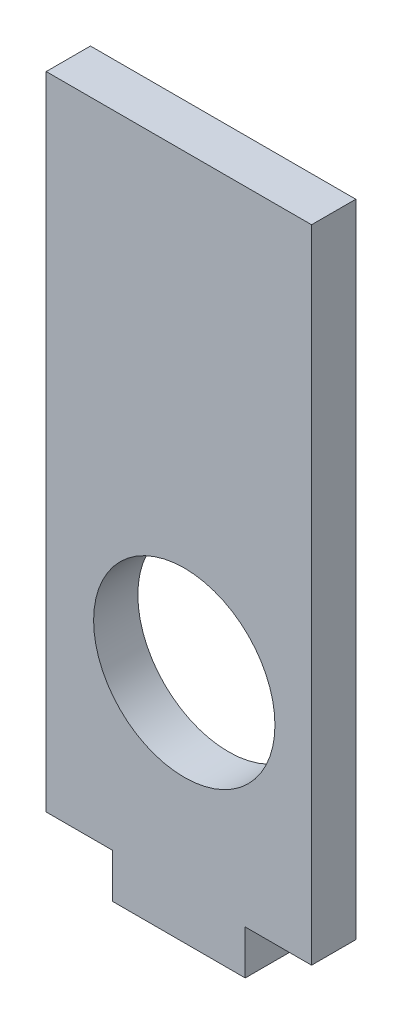
SolidWorks part; units mm, degrees
ref_plane "前视基准面" through (0, 0, 0) normal (0, 0, 1) x (1, 0, 0)
ref_plane "上视基准面" through (0, 0, 0) normal (0, 1, 0) x (1, 0, 0)
ref_plane "右视基准面" through (0, 0, 0) normal (1, 0, 0) x (0, 0, -1)
sketch "草图1" plane through (0, 0, 0) normal (0, 0, 1) x (1, 0, 0)
  line L0 (-6, 0) -> (-6, 15)
  line L1 (-6, 0) -> (-3, 0)
  line L3 (6, 0) -> (6, 15)
  line L4 (-3, 0) -> (-3, -2)
  line L6 (-3, -2) -> (3, -2)
  line L7 (3, 0) -> (3, -2)
  line L8 (-6, 15) -> (-6, 30.0788)
  line L9 (-6, 30.0788) -> (6, 30.0788)
  line L10 (6, 30.0788) -> (6, 15)
  line L11 (3, 0) -> (6, 0)
extrude "凸台-拉伸1" add sketch "草图1" along normal blind 2 contours L9 L10 L3 L11 L7 L6 L4 L1 L0 L8
sketch3d "3D草图1"
  spline S0 degree 3 poles (-3.7284, 8.6867, 2) (-3.7078, 8.161, 2) (-3.6722, 7.9035, 2) (-3.5524, 7.3986, 2) (-3.467, 7.1488, 2) (-3.2505, 6.6735, 2) (-3.1206, 6.4491, 2) (-2.8176, 6.0262, 2) (-2.6428, 5.8268, 2) (-2.2635, 5.4714, 2) (-2.0578, 5.3133, 2) (-1.6138, 5.037, 2) (-1.3773, 4.9208, 2) (-0.8916, 4.7388, 2) (-0.639, 4.6715, 2) (-0.1207, 4.5878, 2) (0.1386, 4.5724, 2) (0.6574, 4.5924, 2) (0.9199, 4.6288, 2) (1.4263, 4.7517, 2) (1.6711, 4.8374, 2) (2.144, 5.0577, 2) (2.3715, 5.1927, 2) (2.7898, 5.5003, 2) (2.9832, 5.6739, 2) (3.3378, 6.0622, 2) (3.4935, 6.271, 2) (3.7622, 6.715, 2) (3.8764, 6.9531, 2) (4.055, 7.4439, 2) (4.1196, 7.6952, 2) (4.2002, 8.2093, 2) (4.2156, 8.4739, 2) (4.1954, 8.9933, 2) (4.1605, 9.2504, 2) (4.0401, 9.7595, 2) (3.9548, 10.0085, 2) (3.7402, 10.4807, 2) (3.6098, 10.7071, 2) (3.304, 11.134, 2) (3.1327, 11.3292, 2) (2.7544, 11.6845, 2) (2.5446, 11.8459, 2) (2.1019, 12.1214, 2) (1.8693, 12.2361, 2) (1.3817, 12.4193, 2) (1.1256, 12.4874, 2) (0.6129, 12.5704, 2) (0.3537, 12.5866, 2) (-0.1705, 12.5666, 2) (-0.4299, 12.5305, 2) (-0.9342, 12.4086, 2) (-1.1829, 12.3219, 2) (-1.6571, 12.101, 2) (-1.8803, 11.9687, 2) (-2.2997, 11.661, 2) (-2.497, 11.4837, 2) (-2.8478, 11.0998, 2) (-3.0034, 10.8921, 2) (-3.2746, 10.4448, 2) (-3.3883, 10.2072, 2) (-3.5662, 9.7198, 2) (-3.6318, 9.4669, 2) (-3.7132, 8.9479, 2) (-3.7284, 8.6867, 2) (-3.7078, 8.161, 2) (-3.6722, 7.9035, 2) knots -0.03125 -0.03125 0 0 0.03125 0.03125 0.0625 0.0625 0.09375 0.09375 0.125 0.125 0.15625 0.15625 0.1875 0.1875 0.21875 0.21875 0.25 0.25 0.28125 0.28125 0.3125 0.3125 0.34375 0.34375 0.375 0.375 0.40625 0.40625 0.4375 0.4375 0.46875 0.46875 0.5 0.5 0.53125 0.53125 0.5625 0.5625 0.59375 0.59375 0.625 0.625 0.65625 0.65625 0.6875 0.6875 0.71875 0.71875 0.75 0.75 0.78125 0.78125 0.8125 0.8125 0.84375 0.84375 0.875 0.875 0.90625 0.90625 0.9375 0.9375 0.96875 0.96875 1 1 1.03125 1.03125 1.0625 only from (-3.7181, 8.4239, 2) to (-3.7181, 8.4239, 2)
  spline S1 degree 3 poles (-3.7284, 8.6867, 2) (-3.7078, 8.161, 2) (-3.6722, 7.9035, 2) (-3.5524, 7.3986, 2) (-3.467, 7.1488, 2) (-3.2505, 6.6735, 2) (-3.1206, 6.4491, 2) (-2.8176, 6.0262, 2) (-2.6428, 5.8268, 2) (-2.2635, 5.4714, 2) (-2.0578, 5.3133, 2) (-1.6138, 5.037, 2) (-1.3773, 4.9208, 2) (-0.8916, 4.7388, 2) (-0.639, 4.6715, 2) (-0.1207, 4.5878, 2) (0.1386, 4.5724, 2) (0.6574, 4.5924, 2) (0.9199, 4.6288, 2) (1.4263, 4.7517, 2) (1.6711, 4.8374, 2) (2.144, 5.0577, 2) (2.3715, 5.1927, 2) (2.7898, 5.5003, 2) (2.9832, 5.6739, 2) (3.3378, 6.0622, 2) (3.4935, 6.271, 2) (3.7622, 6.715, 2) (3.8764, 6.9531, 2) (4.055, 7.4439, 2) (4.1196, 7.6952, 2) (4.2002, 8.2093, 2) (4.2156, 8.4739, 2) (4.1954, 8.9933, 2) (4.1605, 9.2504, 2) (4.0401, 9.7595, 2) (3.9548, 10.0085, 2) (3.7402, 10.4807, 2) (3.6098, 10.7071, 2) (3.304, 11.134, 2) (3.1327, 11.3292, 2) (2.7544, 11.6845, 2) (2.5446, 11.8459, 2) (2.1019, 12.1214, 2) (1.8693, 12.2361, 2) (1.3817, 12.4193, 2) (1.1256, 12.4874, 2) (0.6129, 12.5704, 2) (0.3537, 12.5866, 2) (-0.1705, 12.5666, 2) (-0.4299, 12.5305, 2) (-0.9342, 12.4086, 2) (-1.1829, 12.3219, 2) (-1.6571, 12.101, 2) (-1.8803, 11.9687, 2) (-2.2997, 11.661, 2) (-2.497, 11.4837, 2) (-2.8478, 11.0998, 2) (-3.0034, 10.8921, 2) (-3.2746, 10.4448, 2) (-3.3883, 10.2072, 2) (-3.5662, 9.7198, 2) (-3.6318, 9.4669, 2) (-3.7132, 8.9479, 2) (-3.7284, 8.6867, 2) (-3.7078, 8.161, 2) (-3.6722, 7.9035, 2) knots -0.03125 -0.03125 0 0 0.03125 0.03125 0.0625 0.0625 0.09375 0.09375 0.125 0.125 0.15625 0.15625 0.1875 0.1875 0.21875 0.21875 0.25 0.25 0.28125 0.28125 0.3125 0.3125 0.34375 0.34375 0.375 0.375 0.40625 0.40625 0.4375 0.4375 0.46875 0.46875 0.5 0.5 0.53125 0.53125 0.5625 0.5625 0.59375 0.59375 0.625 0.625 0.65625 0.65625 0.6875 0.6875 0.71875 0.71875 0.75 0.75 0.78125 0.78125 0.8125 0.8125 0.84375 0.84375 0.875 0.875 0.90625 0.90625 0.9375 0.9375 0.96875 0.96875 1 1 1.03125 1.03125 1.0625 only from (-3.7181, 8.4239, 2) to (-3.7181, 8.4239, 2)
sketch "草图2" plane through (0, 0, 2) normal (0, 0, 1) x (1, 0, 0)
  line L0 (4.2085, 4.5794) -> (0.2436, 8.5794)
  line L1 (4.2085, 12.5795) -> (-3.7212, 12.5795)
  line L2 (4.2085, 12.5795) -> (4.2085, 4.5794)
  line L3 (4.2085, 4.5794) -> (-3.7212, 4.5794)
  line L4 (-3.7212, 12.5795) -> (-3.7212, 4.5794)
  line L5 (4.2085, 12.5795) -> (3.0462, 11.4069)
  line L6 (0.2436, 8.5794) -> (-3.7212, 4.5794)
  line L7 (-2.5609, 11.4088) -> (-3.7212, 12.5795)
  line L8 (-6, 30.0788) -> (-6, 0)
  line L9 (-6, 0) -> (-3, 0)
  line L10 (-3, 0) -> (-3, -2)
  line L11 (-3, -2) -> (3, -2)
  line L12 (3, -2) -> (3, 0)
  line L13 (3, 0) -> (6, 0)
  line L14 (6, 0) -> (6, 30.0788)
  line L15 (6, 30.0788) -> (-6, 30.0788)
  line L16 (-6, 30.0788) -> (-6, 0)
  line L17 (-6, 0) -> (-3, 0)
  line L18 (-3, 0) -> (-3, -2)
  line L19 (-3, -2) -> (3, -2)
  line L20 (3, -2) -> (3, 0)
  line L21 (3, 0) -> (6, 0)
  line L22 (6, 0) -> (6, 30.0788)
  line L23 (6, 30.0788) -> (-6, 30.0788)
  circle A0 centre (0.2436, 8.5794) radius 4.1
  spline S0 degree 3 poles (-3.7284, 8.6867) (-3.7078, 8.161) (-3.6722, 7.9035) (-3.5524, 7.3986) (-3.467, 7.1488) (-3.2505, 6.6735) (-3.1206, 6.4491) (-2.8176, 6.0262) (-2.6428, 5.8268) (-2.2635, 5.4714) (-2.0578, 5.3133) (-1.6138, 5.037) (-1.3773, 4.9208) (-0.8916, 4.7388) (-0.639, 4.6715) (-0.1207, 4.5878) (0.1386, 4.5724) (0.6574, 4.5924) (0.9199, 4.6288) (1.4263, 4.7517) (1.6711, 4.8374) (2.144, 5.0577) (2.3715, 5.1927) (2.7898, 5.5003) (2.9832, 5.6739) (3.3378, 6.0622) (3.4935, 6.271) (3.7622, 6.715) (3.8764, 6.9531) (4.055, 7.4439) (4.1196, 7.6952) (4.2002, 8.2093) (4.2156, 8.4739) (4.1954, 8.9933) (4.1605, 9.2504) (4.0401, 9.7595) (3.9548, 10.0085) (3.7402, 10.4807) (3.6098, 10.7071) (3.304, 11.134) (3.1327, 11.3292) (2.7544, 11.6845) (2.5446, 11.8459) (2.1019, 12.1214) (1.8693, 12.2361) (1.3817, 12.4193) (1.1256, 12.4874) (0.6129, 12.5704) (0.3537, 12.5866) (-0.1705, 12.5666) (-0.4299, 12.5305) (-0.9342, 12.4086) (-1.1829, 12.3219) (-1.6571, 12.101) (-1.8803, 11.9687) (-2.2997, 11.661) (-2.497, 11.4837) (-2.8478, 11.0998) (-3.0034, 10.8921) (-3.2746, 10.4448) (-3.3883, 10.2072) (-3.5662, 9.7198) (-3.6318, 9.4669) (-3.7132, 8.9479) (-3.7284, 8.6867) (-3.7078, 8.161) (-3.6722, 7.9035) knots -0.03125 -0.03125 0 0 0.03125 0.03125 0.0625 0.0625 0.09375 0.09375 0.125 0.125 0.15625 0.15625 0.1875 0.1875 0.21875 0.21875 0.25 0.25 0.28125 0.28125 0.3125 0.3125 0.34375 0.34375 0.375 0.375 0.40625 0.40625 0.4375 0.4375 0.46875 0.46875 0.5 0.5 0.53125 0.53125 0.5625 0.5625 0.59375 0.59375 0.625 0.625 0.65625 0.65625 0.6875 0.6875 0.71875 0.71875 0.75 0.75 0.78125 0.78125 0.8125 0.8125 0.84375 0.84375 0.875 0.875 0.90625 0.90625 0.9375 0.9375 0.96875 0.96875 1 1 1.03125 1.03125 1.0625 only from (-3.7181, 8.4239) to (-3.7181, 8.4239) construction
  spline S1 degree 3 poles (-3.7284, 8.6867) (-3.7078, 8.161) (-3.6722, 7.9035) (-3.5524, 7.3986) (-3.467, 7.1488) (-3.2505, 6.6735) (-3.1206, 6.4491) (-2.8176, 6.0262) (-2.6428, 5.8268) (-2.2635, 5.4714) (-2.0578, 5.3133) (-1.6138, 5.037) (-1.3773, 4.9208) (-0.8916, 4.7388) (-0.639, 4.6715) (-0.1207, 4.5878) (0.1386, 4.5724) (0.6574, 4.5924) (0.9199, 4.6288) (1.4263, 4.7517) (1.6711, 4.8374) (2.144, 5.0577) (2.3715, 5.1927) (2.7898, 5.5003) (2.9832, 5.6739) (3.3378, 6.0622) (3.4935, 6.271) (3.7622, 6.715) (3.8764, 6.9531) (4.055, 7.4439) (4.1196, 7.6952) (4.2002, 8.2093) (4.2156, 8.4739) (4.1954, 8.9933) (4.1605, 9.2504) (4.0401, 9.7595) (3.9548, 10.0085) (3.7402, 10.4807) (3.6098, 10.7071) (3.304, 11.134) (3.1327, 11.3292) (2.7544, 11.6845) (2.5446, 11.8459) (2.1019, 12.1214) (1.8693, 12.2361) (1.3817, 12.4193) (1.1256, 12.4874) (0.6129, 12.5704) (0.3537, 12.5866) (-0.1705, 12.5666) (-0.4299, 12.5305) (-0.9342, 12.4086) (-1.1829, 12.3219) (-1.6571, 12.101) (-1.8803, 11.9687) (-2.2997, 11.661) (-2.497, 11.4837) (-2.8478, 11.0998) (-3.0034, 10.8921) (-3.2746, 10.4448) (-3.3883, 10.2072) (-3.5662, 9.7198) (-3.6318, 9.4669) (-3.7132, 8.9479) (-3.7284, 8.6867) (-3.7078, 8.161) (-3.6722, 7.9035) knots -0.03125 -0.03125 0 0 0.03125 0.03125 0.0625 0.0625 0.09375 0.09375 0.125 0.125 0.15625 0.15625 0.1875 0.1875 0.21875 0.21875 0.25 0.25 0.28125 0.28125 0.3125 0.3125 0.34375 0.34375 0.375 0.375 0.40625 0.40625 0.4375 0.4375 0.46875 0.46875 0.5 0.5 0.53125 0.53125 0.5625 0.5625 0.59375 0.59375 0.625 0.625 0.65625 0.65625 0.6875 0.6875 0.71875 0.71875 0.75 0.75 0.78125 0.78125 0.8125 0.8125 0.84375 0.84375 0.875 0.875 0.90625 0.90625 0.9375 0.9375 0.96875 0.96875 1 1 1.03125 1.03125 1.0625 only from (-3.7181, 8.4239) to (-3.7181, 8.4239)
  dimension "D1" = 0
extrude "切除-拉伸1" cut sketch "草图2" against normal blind 10 contours A0
sketch "草图3" plane through (0, 0, 2) normal (0, 0, 1) x (1, 0, 0)
  line L0 (17.7523, 29) -> (-31.8073, 29) construction
  line L1 (17.7523, 29) -> (-31.8073, 29)
  line L2 (10.2989, 29) -> (10.2989, 34.1435)
  line L3 (10.2989, 34.1435) -> (-9.585, 34.1435)
  line L4 (-9.585, 34.1435) -> (-9.585, 29)
  line M2 (-6, 30.0788) -> (-6, 0)
  line M8 (6, 0) -> (6, 30.0788)
  line M9 (6, 30.0788) -> (-6, 30.0788)
extrude "切除-拉伸2" cut sketch "草图3" against normal blind 10 contours L1 M8 M9 M2 | L3 L4 L1 L2 M2 M9 M8
